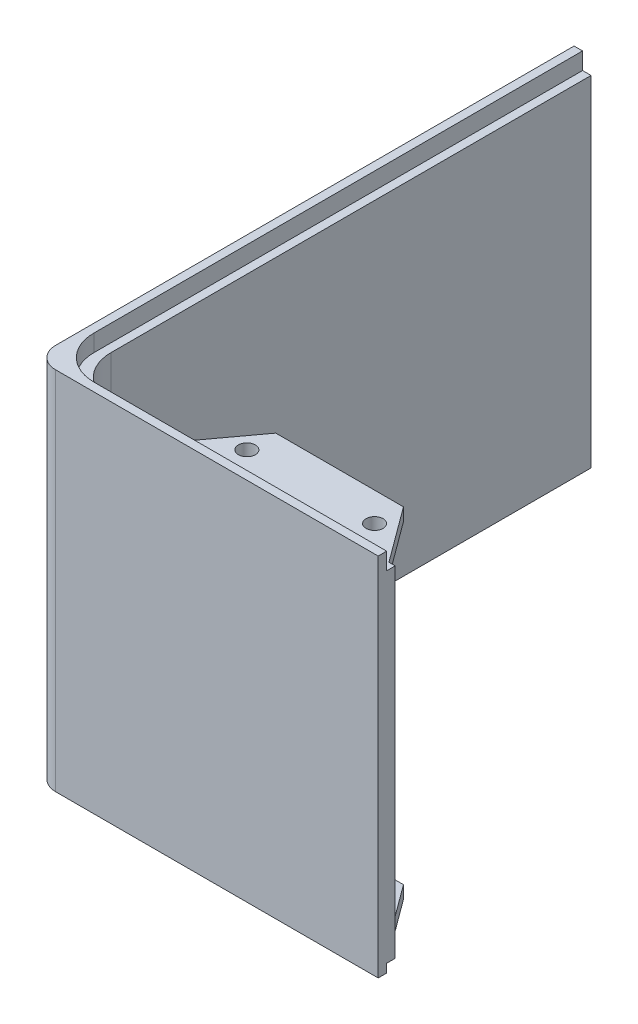
SolidWorks part; units mm, degrees
material "PLA (general purpose)"
ref_plane "Alzado" through (0, 0, 0) normal (0, 0, 1) x (1, 0, 0)
ref_plane "Planta" through (0, 0, 0) normal (0, 1, 0) x (1, 0, 0)
ref_plane "Vista lateral" through (0, 0, 0) normal (1, 0, 0) x (0, 0, -1)
sketch "Croquis1" plane through (0, 0, 0) normal (0, 0, 1) x (1, 0, 0)
  line L0 (1, 39) -> (1, 43)
  line L1 (-1, -43) -> (1, -43)
  line L2 (-1, -43) -> (-1, 43)
  line L3 (-1, 43) -> (1, 43)
  line L4 (1, -43) -> (1, -41)
  line L5 (-1, -43) -> (1, 43) construction
  line L6 (-1, 43) -> (1, -43) construction
  line L7 (3, -41) -> (1, -41)
  line L8 (3, -41) -> (3, 39)
  line L9 (3, 39) -> (1, 39)
  line L11 (3, -41) -> (1, 39) construction
  line L12 (3, 39) -> (1, -41) construction
  point P0 (0, 0)
  point P6 (2, -1)
  dimension "D1" = 86
  dimension "D2" = 2
  dimension "D3" = 2
  dimension "D4" = 4
  dimension "D5" = 80
extrude "Saliente-Extruir1" add sketch "Croquis1" along normal blind 123
sketch "Croquis2" plane through (0, 0, 123) normal (0, 0, 1) x (1, 0, 0)
  line L1 (79.9, -43) -> (-1, -43)
  line L2 (79.9, -43) -> (79.9, 43)
  line L3 (79.9, 43) -> (-1, 43)
  line L4 (-1, -43) -> (-1, 43)
  line L5 (79.9, -43) -> (-1, 43) construction
  line L6 (79.9, 43) -> (-1, -43) construction
  point P0 (39.45, 0)
  dimension "D1" = 80.9
extrude "Saliente-Extruir2" add sketch "Croquis2" along normal blind 4
sketch "Croquis3" plane through (79.9, 0, 0) normal (1, 0, 0) x (0, 0, -1)
  line L1 (-125, 39) -> (-123, 39)
  line L2 (-125, 39) -> (-125, 43)
  line L3 (-125, 43) -> (-123, 43)
  line L4 (-123, 39) -> (-123, 43)
  line L5 (-125, 39) -> (-123, 43) construction
  line L6 (-125, 43) -> (-123, 39) construction
  line L7 (-125, -43) -> (-123, -43)
  line L8 (-125, -43) -> (-125, -41)
  line L9 (-125, -41) -> (-123, -41)
  line L10 (-123, -43) -> (-123, -41)
  line L11 (-125, -43) -> (-123, -41) construction
  line L12 (-125, -41) -> (-123, -43) construction
  point P0 (-124, 41)
  point P6 (-124, -42)
  dimension "D1" = 2
  dimension "D2" = 4
  dimension "D3" = 2
  dimension "D4" = 2
extrude "Cortar-Extruir1" cut sketch "Croquis3" against normal up to surface (78.9 mm away) up to face at (1, 41, 61.5)
fillet "Redondeo1" radius 5 1 edges at (-1, 0, 127)
fillet "Redondeo2" radius 10 3 edges at (1, -42, 125) (3, -1, 123) (1, 41, 125)
sketch "Croquis4" plane through (0, -41, 0) normal (0, -1, 0) x (1, 0, 0)
  line L0 (11, 125) -> (79.9, 125) construction
  line L1 (38.8, 110) -> (68.85, 110)
  line L2 (38.8, 110) -> (38.8, 125)
  line L3 (38.8, 125) -> (68.85, 125)
  line L4 (68.85, 110) -> (68.85, 125)
  line L5 (38.8, 110) -> (68.85, 125) construction
  line L6 (38.8, 125) -> (68.85, 110) construction
  line L7 (1, 115) -> (1, 0) construction
  line L8 (38.8, 110) -> (27.7491, 125)
  line L9 (27.7491, 125) -> (38.8, 125)
  line L10 (68.85, 110) -> (79.9, 125)
  line L11 (79.9, 127) -> (79.9, 125) construction
  line L12 (79.9, 125) -> (68.85, 125)
  point P0 (53.825, 117.5)
  line M15 (13, 123) -> (79.9, 123)
  dimension "D1" = 37.8
  dimension "D2" = 30.05
  dimension "D3" = 15
  dimension "D4" = 53.62
extrude "Saliente-Extruir3" add sketch "Croquis4" against normal blind 3 contours L1 L4 L2 M15 | L8 L2 M15 | L4 L10 M15
sketch "Croquis5" plane through (0, -38, 0) normal (0, 1, 0) x (1, 0, 0)
  line L0 (1, -115) -> (1, 0) construction
  line L1 (11, -125) -> (79.9, -125) construction
  line L2 (38.8, -110) -> (68.85, -110) construction
  circle A0 centre (38.8, -116.8) radius 2
  circle A1 centre (68.85, -116.8) radius 2
  dimension "D4" = 4
  dimension "D5" = 4
  dimension "D1" = 30.05
  dimension "D2" = 37.8
  dimension "D3" = 8.2
  dimension "D6" = 6.8
extrude "Cortar-Extruir2" cut sketch "Croquis5" against normal blind 3
ref_plane "Plano1" through (0, -1, 0) normal (0, -1, 0) x (-1, 0, 0)
mirror "Simetría1" about plane through (0, -1, 0) normal (0, -1, 0) of "Cortar-Extruir2", "Saliente-Extruir3"
